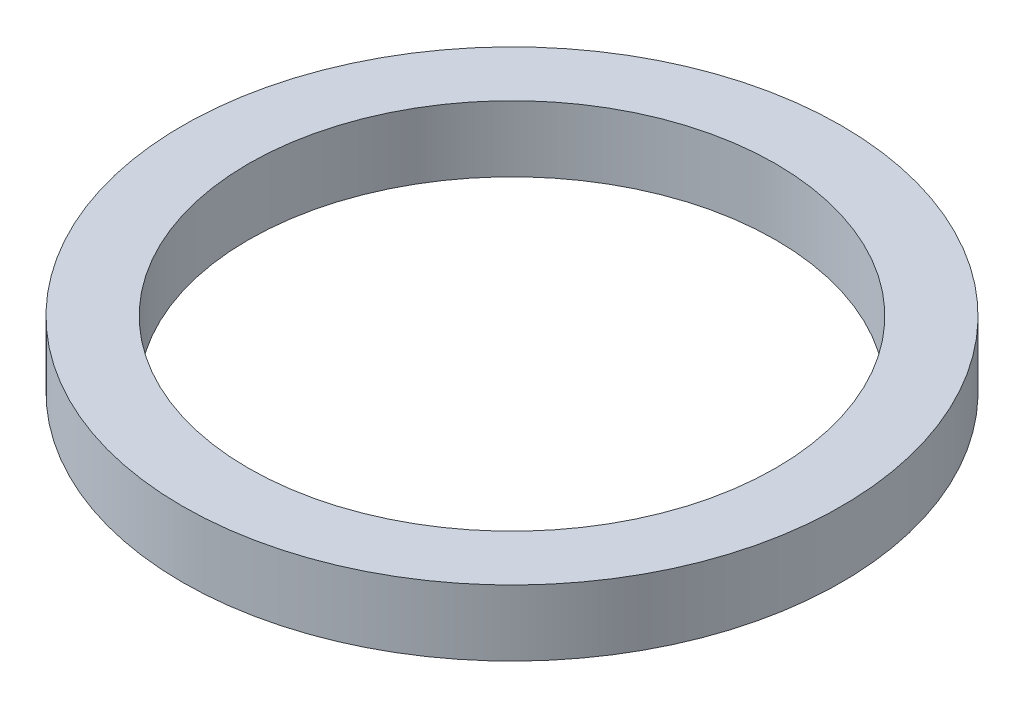
SolidWorks part; units mm, degrees
material "BUTYL"
ref_plane "前视基准面" through (0, 0, 0) normal (0, 0, 1) x (1, 0, 0)
ref_plane "上视基准面" through (0, 0, 0) normal (0, 1, 0) x (1, 0, 0)
ref_plane "右视基准面" through (0, 0, 0) normal (1, 0, 0) x (0, 0, -1)
other "Configuration Table"
sketch "草图1" plane through (0, 0, 0) normal (0, 1, 0) x (1, 0, 0)
  circle A0 centre (0, 0) radius 20
  circle A1 centre (0, 0) radius 25
  dimension "D1" = 40
  dimension "D2" = 50
extrude "凸台-拉伸1" add sketch "草图1" along normal blind 5
